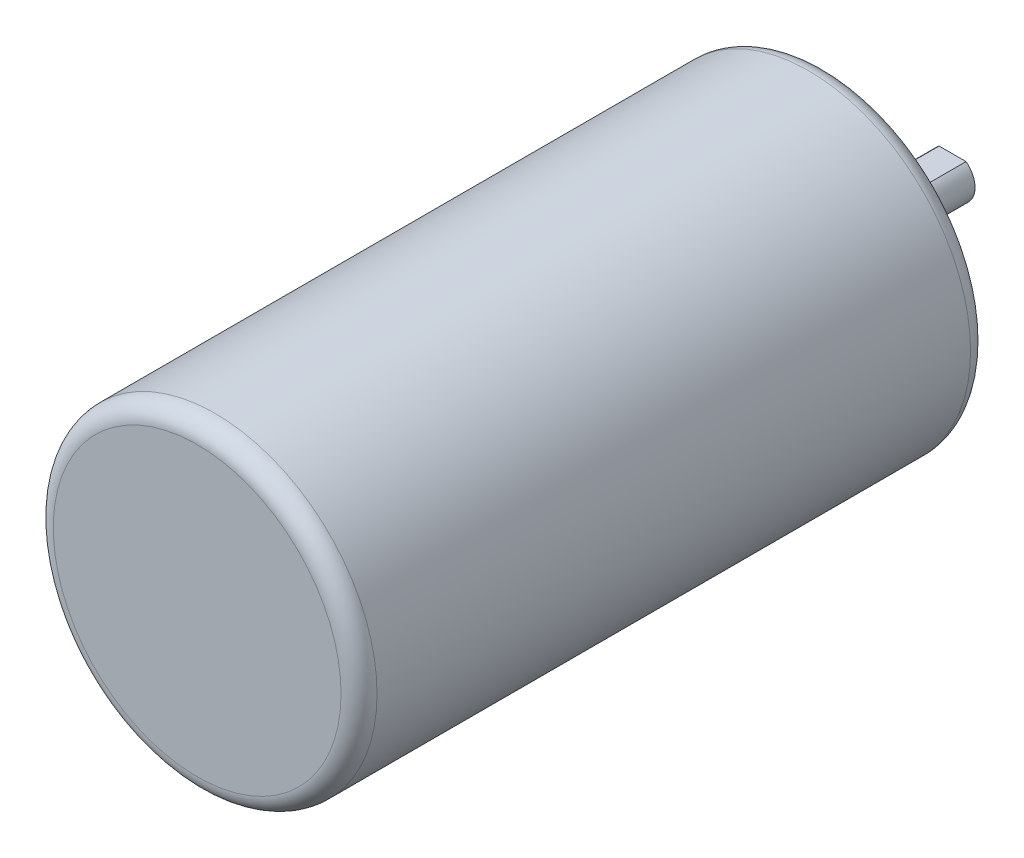
SolidWorks part; units mm, degrees
ref_plane "Front Plane" through (0, 0, 0) normal (0, 0, 1) x (1, 0, 0)
ref_plane "Top Plane" through (0, 0, 0) normal (0, 1, 0) x (1, 0, 0)
ref_plane "Right Plane" through (0, 0, 0) normal (1, 0, 0) x (0, 0, -1)
sketch "Sketch1" plane through (0, 0, 0) normal (0, 0, 1) x (1, 0, 0)
  circle A0 centre (0, 0) radius 18
  dimension "D1" = 36
extrude "Boss-Extrude1" add sketch "Sketch1" along normal blind 70
sketch "Sketch2" plane through (0, 0, 0) normal (0, 0, -1) x (-1, 0, 0)
  line L0 (-1.5, 2) -> (1.5, 2)
  arc A0 (-1.5, 2) -> (1.5, 2) centre (0, 0) ccw
  dimension "D1" = 5
  dimension "D2" = 4.5
extrude "Boss-Extrude2" add sketch "Sketch2" along normal blind 14
fillet "Fillet1" radius 2 2 edges at (18, 0, 70) (18, 0, 0)
sketch "Sketch3" plane through (0, 0, 0) normal (0, 0, -1) x (-1, 0, 0)
  circle A0 centre (0, 0) radius 12.5 construction
  circle A1 centre (-12.5, 0) radius 1.5
  circle A2 centre (-6.25, 10.8253) radius 1.5
  circle A3 centre (6.25, 10.8253) radius 1.5
  circle A4 centre (12.5, 0) radius 1.5
  circle A5 centre (6.25, -10.8253) radius 1.5
  circle A6 centre (-6.25, -10.8253) radius 1.5
  point P17 (0, 0)
  dimension "D1" = 25
  dimension "D2" = 3
  dimension "D3" = 6
extrude "Cut-Extrude1" cut sketch "Sketch3" against normal blind 10
